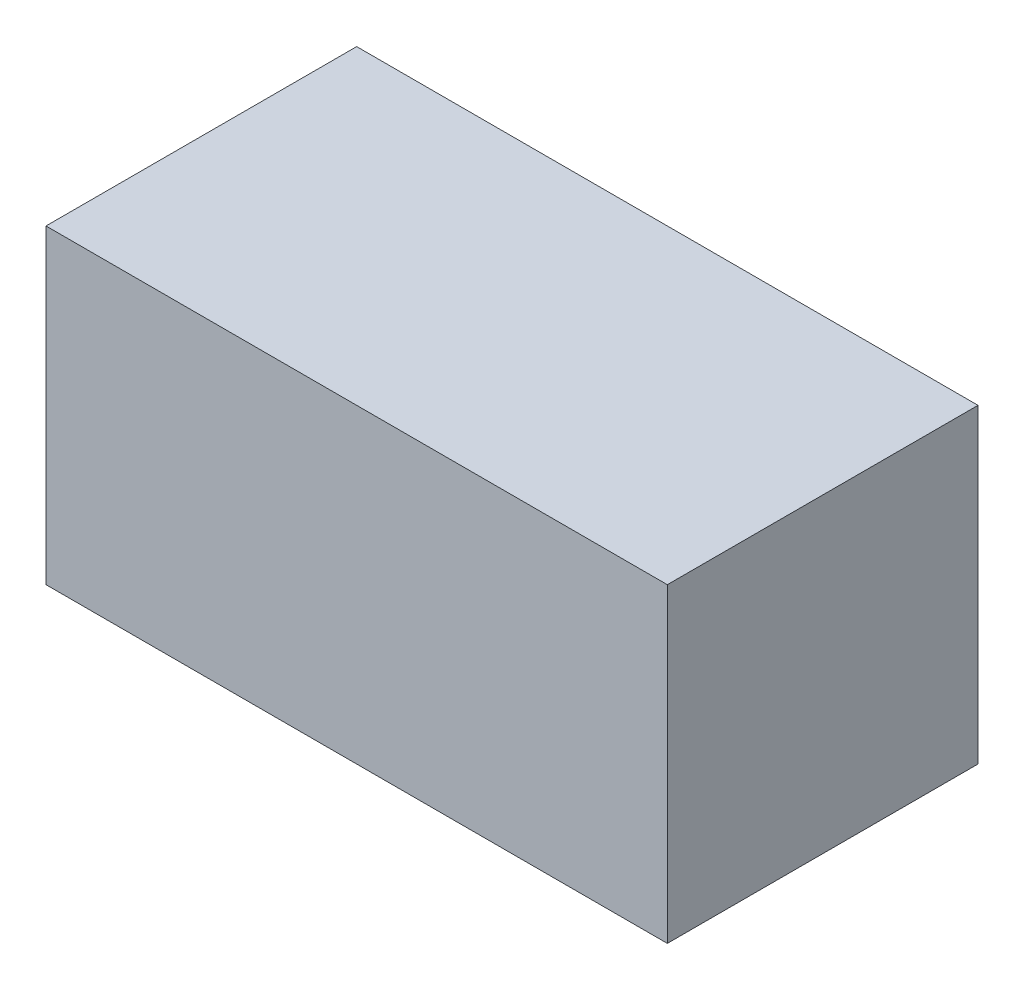
SolidWorks part; units mm, degrees
ref_plane "Front Plane" through (0, 0, 0) normal (0, 0, 1) x (1, 0, 0)
ref_plane "Top Plane" through (0, 0, 0) normal (0, 1, 0) x (1, 0, 0)
ref_plane "Right Plane" through (0, 0, 0) normal (1, 0, 0) x (0, 0, -1)
sketch "Sketch1" plane through (0, 0, 0) normal (0, 1, 0) x (1, 0, 0)
  line L1 (0, 0) -> (20, 0)
  line L2 (0, 0) -> (0, 10)
  line L3 (0, 10) -> (20, 10)
  line L4 (20, 0) -> (20, 10)
  dimension "D1" = 10
  dimension "D2" = 20
extrude "Boss-Extrude1" add sketch "Sketch1" along normal blind 10
